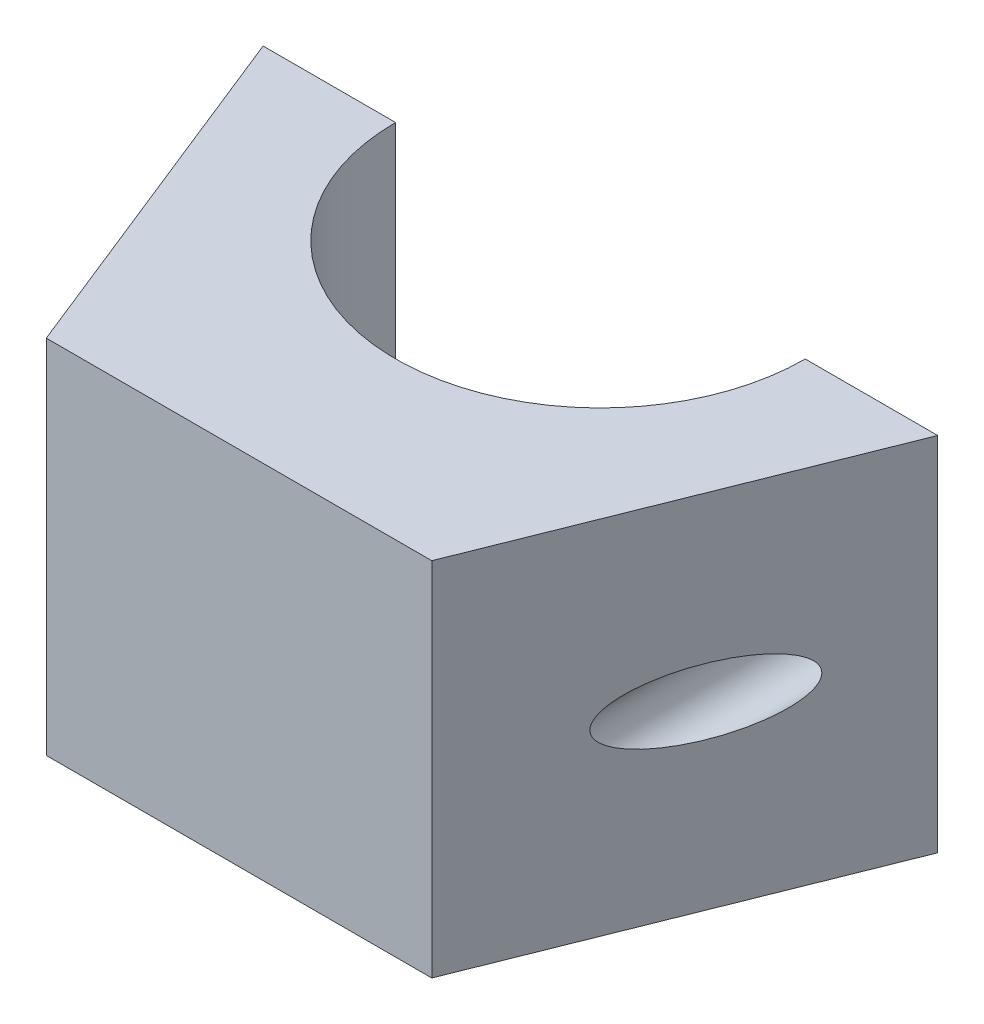
SolidWorks part; units mm, degrees
ref_plane "Front Plane" through (0, 0, 0) normal (0, 0, 1) x (1, 0, 0)
ref_plane "Top Plane" through (0, 0, 0) normal (0, 1, 0) x (1, 0, 0)
ref_plane "Right Plane" through (0, 0, 0) normal (1, 0, 0) x (0, 0, -1)
sketch "Sketch1" plane through (0, 0, 0) normal (0, 1, 0) x (1, 0, 0)
  line L1 (-34.8162, 18.0331) -> (5.1838, 18.0331)
  line L2 (-34.8162, 18.0331) -> (-34.8162, -11.9669)
  line L3 (-34.8162, -11.9669) -> (5.1838, -11.9669)
  line L4 (5.1838, 18.0331) -> (5.1838, -11.9669)
  line L5 (-14.8162, -11.9669) -> (-14.8162, 18.0331) construction
  line L6 (-34.8162, 3.0331) -> (5.1838, 3.0331) construction
  point P0 (-14.8162, 3.0331)
  dimension "D1" = 40
  dimension "D2" = 30
extrude "Boss-Extrude1" add sketch "Sketch1" along normal blind 15
sketch "Sketch2" plane through (0, 15, 0) normal (0, 1, 0) x (1, 0, 0)
  line L0 (-34.8162, 3.0331) -> (5.1838, 3.0331) construction
  line L1 (-14.8162, 18.0331) -> (-14.8162, -11.9669) construction
  line L2 (-28.8162, 18.0331) -> (-28.8162, -11.9669)
  line L3 (-0.8162, 18.0331) -> (-0.8162, -11.9669)
  line L4 (5.1838, -11.9669) -> (5.1838, 18.0331)
  line L5 (5.1838, 18.0331) -> (-34.8162, 18.0331)
  line L6 (-34.8162, 18.0331) -> (-34.8162, -11.9669)
  line L7 (-34.8162, -11.9669) -> (5.1838, -11.9669)
  line L8 (5.1838, -11.9669) -> (5.1838, 18.0331)
  line L9 (5.1838, 18.0331) -> (-34.8162, 18.0331)
  line L10 (-34.8162, 18.0331) -> (-34.8162, -11.9669)
  line L11 (-34.8162, -11.9669) -> (5.1838, -11.9669)
  line L12 (-34.8162, 18.0331) -> (-28.8162, 3.0331)
  line L13 (-28.8162, 3.0331) -> (-22.8162, -11.9669)
  line L14 (5.1838, 18.0331) -> (-0.8162, 3.0331)
  line L15 (-0.8162, 3.0331) -> (-6.8162, -11.9669)
  line L16 (-28.8162, 3.0331) -> (-23.3162, 3.0331)
  line L17 (-23.3162, 3.0331) -> (-0.8162, 3.0331)
  circle A0 centre (-14.8162, 3.0331) radius 8.5
  line M6 (5.1838, -11.9669) -> (5.1838, 18.0331)
  line M7 (5.1838, 18.0331) -> (-34.8162, 18.0331)
  line M8 (-34.8162, 18.0331) -> (-34.8162, -11.9669)
  line M9 (-34.8162, -11.9669) -> (5.1838, -11.9669)
  dimension "D2" = 17
  dimension "D4" = 6
  dimension "D3" = 6
  dimension "D1" = 0
extrude "Cut-Extrude1" cut sketch "Sketch2" against normal blind 15 contours L12 L2 M7 | A0 L17 L3 L2 L16 M7 | L14 L3 M7 | L14 L3 M6 M9 | L3 L15 M9 | L13 L2 M9 | L12 L2 M8 M9 | L17 A0 | L17 A0
sketch "Sketch3" plane through (0, 0, -3.0331) normal (0, 0, -1) x (-1, 0, 0)
  line L0 (3.5662, 15) -> (3.5662, 0) construction
  line L1 (26.0662, 15) -> (26.0662, 0) construction
  line L2 (0.8162, 0) -> (0.8162, 15) construction
  line L3 (0.8162, 7.5) -> (28.8162, 7.5) construction
  line L4 (28.8162, 15) -> (23.3162, 15)
  line L5 (23.3162, 15) -> (23.3162, 0)
  line L6 (23.3162, 0) -> (28.8162, 0)
  line L7 (28.8162, 0) -> (28.8162, 15)
  line L8 (28.8162, 15) -> (23.3162, 15)
  line L9 (23.3162, 15) -> (23.3162, 0)
  line L10 (23.3162, 0) -> (28.8162, 0)
  line L11 (28.8162, 0) -> (28.8162, 15)
  line L12 (6.3162, 15) -> (0.8162, 15)
  line L13 (0.8162, 15) -> (0.8162, 0)
  line L14 (0.8162, 0) -> (6.3162, 0)
  line L15 (6.3162, 0) -> (6.3162, 15)
  line L16 (6.3162, 15) -> (0.8162, 15)
  line L17 (0.8162, 5.0123) -> (0.8162, 0)
  line L18 (0.8162, 0) -> (6.3162, 0)
  line L19 (6.3162, 0) -> (6.3162, 15)
  line L20 (3.5662, 7.5) -> (3.5662, 15) construction
  line L21 (0.8162, 7.5) -> (0.8162, 15) construction
  line L22 (0.8162, 15) -> (0.8162, 11.25) construction
  line L23 (0.8162, 11.25) -> (3.5662, 11.25) construction
  circle A6 centre (3.5662, 7.5) radius 1.375
  circle A7 centre (26.0662, 7.5) radius 1.375
  dimension "D3" = 2.75
  dimension "D4" = 2.75
  dimension "D1" = 0
  dimension "D2" = 0
extrude "Cut-Extrude2" cut sketch "Sketch3" against normal blind 15
sketch "Sketch4" plane through (0, 0, 11.9669) normal (0, 0, 1) x (1, 0, 0)
  line L0 (-14.8162, 15) -> (-14.8162, 0) construction
  line L4 (-22.8162, 0) -> (-6.8162, 0)
  line L5 (-6.8162, 0) -> (-6.8162, 15)
  line L6 (-6.8162, 15) -> (-22.8162, 15)
  line L7 (-22.8162, 15) -> (-22.8162, 0)
  line L8 (-22.8162, 0) -> (-6.8162, 0)
  line L9 (-6.8162, 0) -> (-6.8162, 15)
  line L10 (-6.8162, 15) -> (-22.8162, 15)
  line L11 (-22.8162, 15) -> (-22.8162, 0)
  circle A0 centre (-14.8162, 7.5) radius 2
  dimension "D2" = 4
  dimension "D1" = 0
